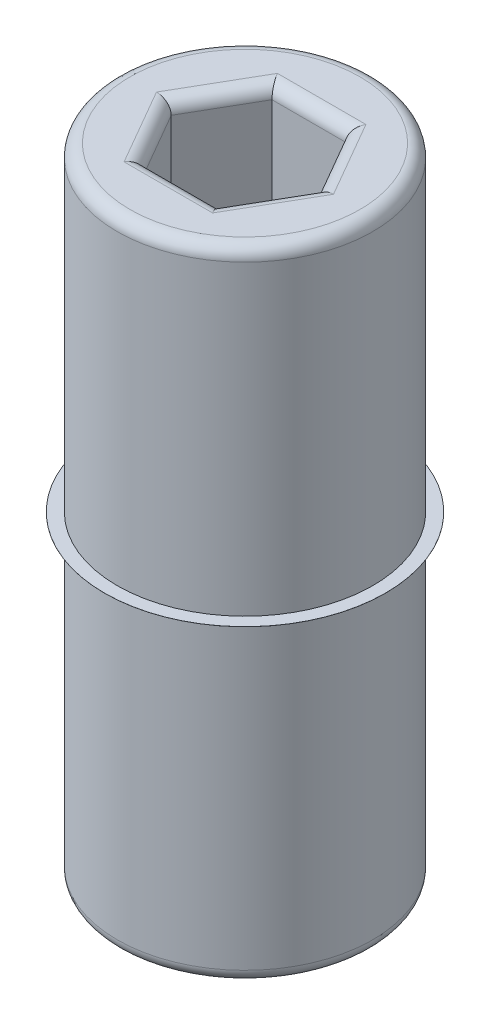
SolidWorks part; units mm, degrees
material "铸造碳钢"
ref_plane "前视基准面" through (0, 0, 0) normal (0, 0, 1) x (1, 0, 0)
ref_plane "上视基准面" through (0, 0, 0) normal (0, 1, 0) x (1, 0, 0)
ref_plane "右视基准面" through (0, 0, 0) normal (1, 0, 0) x (0, 0, -1)
sketch "草图1" plane through (0, 0, 0) normal (0, 1, 0) x (1, 0, 0)
  circle A0 centre (0, 0) radius 2
  dimension "D1" = 4
extrude "凸台-拉伸1" add sketch "草图1" along normal mid plane 10
sketch "草图3" plane through (0, 5, 0) normal (0, 1, 0) x (1, 0, 0)
  line L1 (1.1547, 0) -> (0.5774, 1)
  line L2 (0.5774, 1) -> (-0.5774, 1)
  line L3 (-0.5774, 1) -> (-1.1547, 0)
  line L4 (-1.1547, 0) -> (-0.5774, -1)
  line L5 (-0.5774, -1) -> (0.5774, -1)
  line L6 (0.5774, -1) -> (1.1547, 0)
  circle A0 centre (0, 0) radius 1 construction
  dimension "D1" = 2
extrude "切除-拉伸1" cut sketch "草图3" against normal blind 1.75
fillet "圆角1" radius 0.2 8 edges at (0, -5, 2) (0, 5, 2) (0.866, 5, -0.5) (-0.866, 5, -0.5) (-0.866, 5, 0.5) (0, 5, 1) (0.866, 5, 0.5) (0, 5, -1)
sketch "草图2" plane through (0, 0, 0) normal (0, 1, 0) x (1, 0, 0)
  circle A0 centre (0, 0) radius 2.2
  circle A1 centre (0, 0) radius 2 construction
  dimension "D1" = 0.2
extrude "凸台-拉伸2" add sketch "草图2" along normal mid plane 0.001
other "冻结***"
